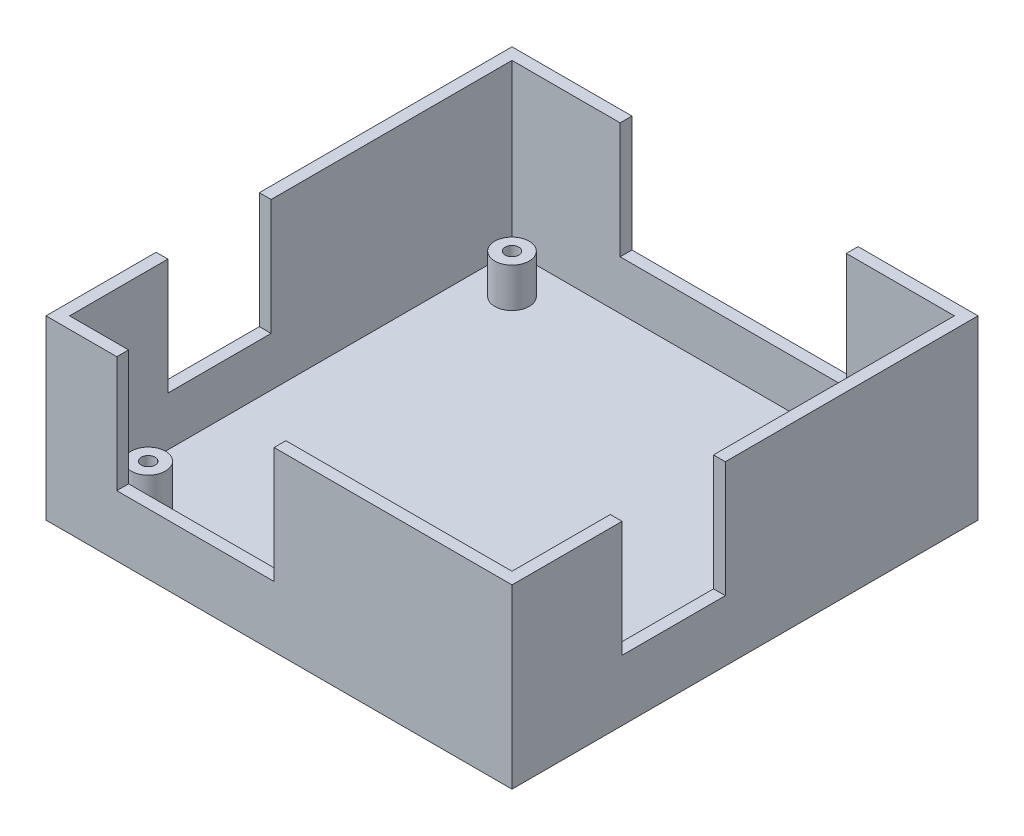
SolidWorks part; units mm, degrees
ref_plane "Front Plane" through (0, 0, 0) normal (0, 0, 1) x (1, 0, 0)
ref_plane "Top Plane" through (0, 0, 0) normal (0, 1, 0) x (1, 0, 0)
ref_plane "Right Plane" through (0, 0, 0) normal (1, 0, 0) x (0, 0, -1)
sketch "Sketch1" plane through (0, 0, 0) normal (0, 1, 0) x (1, 0, 0)
  line L1 (-23.7, 23.7) -> (23.7, 23.7)
  line L2 (-23.7, 23.7) -> (-23.7, -23.7)
  line L3 (-23.7, -23.7) -> (23.7, -23.7)
  line L4 (23.7, 23.7) -> (23.7, -23.7)
  line L5 (-23.7, 23.7) -> (23.7, -23.7) construction
  line L6 (-23.7, -23.7) -> (23.7, 23.7) construction
  point P0 (0, 0)
  dimension "D1" = 47.4
  dimension "D2" = 47.4
extrude "Boss-Extrude1" add sketch "Sketch1" along normal blind 18
sketch "Sketch2" plane through (0, 18, 0) normal (0, 1, 0) x (1, 0, 0)
  line L1 (-22.5, 22.5) -> (22.5, 22.5)
  line L2 (-22.5, 22.5) -> (-22.5, -22.5)
  line L3 (-22.5, -22.5) -> (22.5, -22.5)
  line L4 (22.5, 22.5) -> (22.5, -22.5)
  line L5 (-22.5, 22.5) -> (22.5, -22.5) construction
  line L6 (-22.5, -22.5) -> (22.5, 22.5) construction
  point P0 (0, 0)
  dimension "D1" = 45
  dimension "D2" = 45
extrude "Cut-Extrude1" cut sketch "Sketch2" against normal blind 16.8
sketch "Sketch3" plane through (0, 1.2, 0) normal (0, 1, 0) x (1, 0, 0)
  circle A0 centre (-18.5, 18.5) radius 1.75
  circle A1 centre (18.5, 18.5) radius 1.75
  circle A2 centre (18.5, -18.5) radius 1.75
  circle A3 centre (-18.5, -18.5) radius 1.75
  dimension "D5" = 3.5
  dimension "D6" = 3.5
  dimension "D7" = 3.5
  dimension "D8" = 3.5
  dimension "D1" = 37
  dimension "D2" = 37
  dimension "D3" = 18.5
  dimension "D4" = 18.5
extrude "Boss-Extrude2" add sketch "Sketch3" along normal blind 4
sketch "Sketch4" plane through (0, 5.2, 0) normal (0, 1, 0) x (1, 0, 0)
  circle A0 centre (-18.5, -18.5) radius 0.7
  circle A1 centre (-18.5, 18.5) radius 0.7
  circle A2 centre (18.5, 18.5) radius 0.7
  circle A3 centre (18.5, -18.5) radius 0.7
  dimension "D1" = 1.4
extrude "Cut-Extrude2" cut sketch "Sketch4" against normal blind 3
sketch "Sketch5" plane through (0, 18, 0) normal (0, 1, 0) x (1, 0, 0)
  line L0 (-22.5, -22.5) -> (22.5, -22.5) construction
  line L1 (-16.5, -22.5) -> (-0.5, -22.5)
  line L2 (-16.5, -22.5) -> (-16.5, -23.7)
  line L3 (-16.5, -23.7) -> (-0.5, -23.7)
  line L4 (-0.5, -22.5) -> (-0.5, -23.7)
  line L5 (-23.7, -23.7) -> (23.7, -23.7) construction
  line L6 (23.7, -23.7) -> (23.7, 23.7) construction
  line L7 (22.5, -22.5) -> (22.5, 22.5) construction
  line L8 (22.5, -2) -> (23.7, -2)
  line L9 (22.5, -2) -> (22.5, -12.5)
  line L10 (22.5, -12.5) -> (23.7, -12.5)
  line L11 (23.7, -2) -> (23.7, -12.5)
  line L12 (-22.5, -22.5) -> (22.5, -22.5) construction
  line L13 (-22.5, 22.5) -> (-22.5, -22.5) construction
  line L14 (-22.5, 22.5) -> (-22.5, -22.5) construction
  line L15 (-22.5, -2) -> (-23.7, -2)
  line L16 (-22.5, -2) -> (-22.5, -12.5)
  line L17 (-22.5, -12.5) -> (-23.7, -12.5)
  line L18 (-23.7, -2) -> (-23.7, -12.5)
  line L19 (-23.7, 23.7) -> (-23.7, -23.7) construction
  line L20 (23.7, 23.7) -> (-23.7, 23.7) construction
  line L21 (-11.5, 23.7) -> (11.5, 23.7)
  line L22 (-11.5, 23.7) -> (-11.5, 22.5)
  line L23 (-11.5, 22.5) -> (11.5, 22.5)
  line L24 (11.5, 23.7) -> (11.5, 22.5)
  line L25 (22.5, 22.5) -> (-22.5, 22.5) construction
  dimension "D1" = 16
  dimension "D2" = 6
  dimension "D3" = 10.5
  dimension "D4" = 10
  dimension "D5" = 10.5
  dimension "D6" = 10
  dimension "D7" = 23
  dimension "D8" = 11
extrude "Cut-Extrude3" cut sketch "Sketch5" against normal blind 11.8
